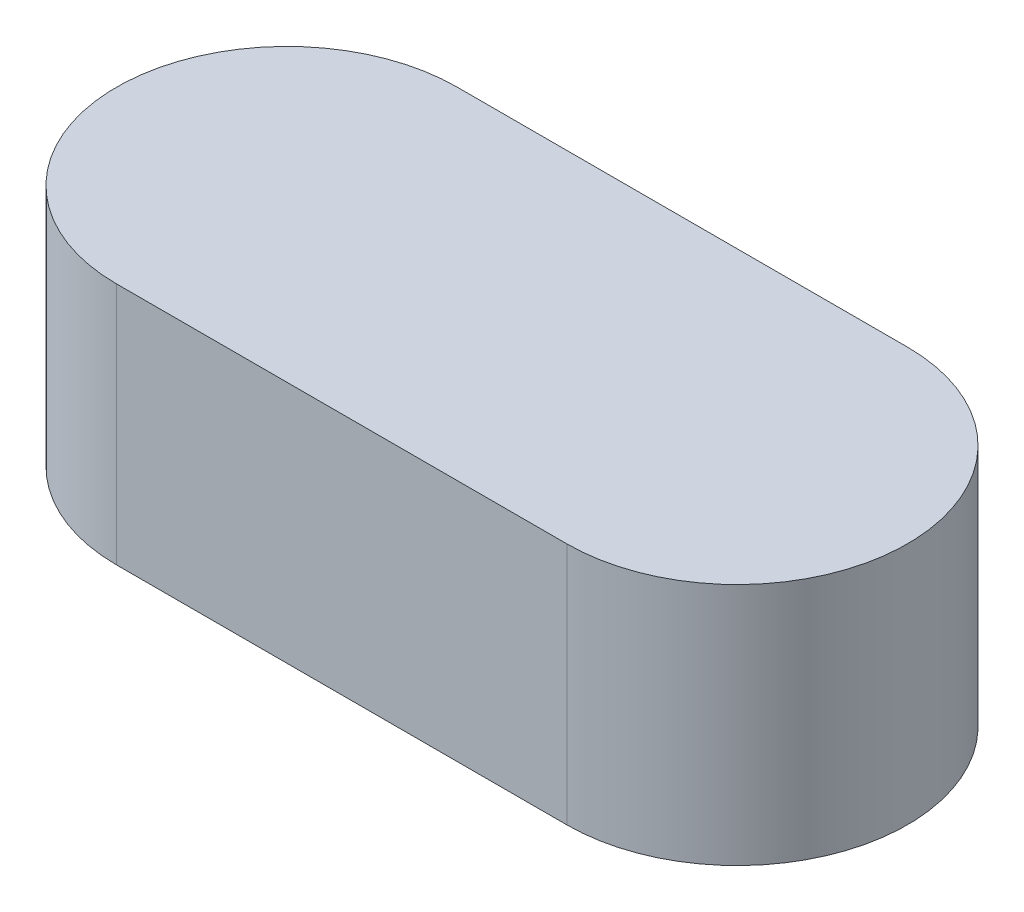
SolidWorks part; units mm, degrees
ref_plane "Front Plane" through (0, 0, 0) normal (0, 0, 1) x (1, 0, 0)
ref_plane "Top Plane" through (0, 0, 0) normal (0, 1, 0) x (1, 0, 0)
ref_plane "Right Plane" through (0, 0, 0) normal (1, 0, 0) x (0, 0, -1)
sketch "Sketch1" plane through (0, 0, 0) normal (0, 1, 0) x (1, 0, 0)
  line L0 (0, 13.0286) -> (0, -11.9327) construction
  line L1 (-18.5, 14) -> (18.5, 14)
  line L2 (-18.5, -14) -> (18.5, -14)
  arc A0 (-18.5, 14) -> (-18.5, -14) centre (-18.5, 0) ccw
  arc A1 (18.5, 14) -> (18.5, -14) centre (18.5, 0) cw
  point P1 (0, 0)
  dimension "D1" = 28
  dimension "D2" = 37
extrude "Boss-Extrude1" add sketch "Sketch1" along normal mid plane 20 contours L1 A1 L2 A0
fillet "Fillet1" [suppressed] radius 10
surface "Surface-Knit1" [suppressed]
ref_plane "Plane1" through (-32.5, 0, 0) normal (-1, 0, 0) x (0, 0, 1)
